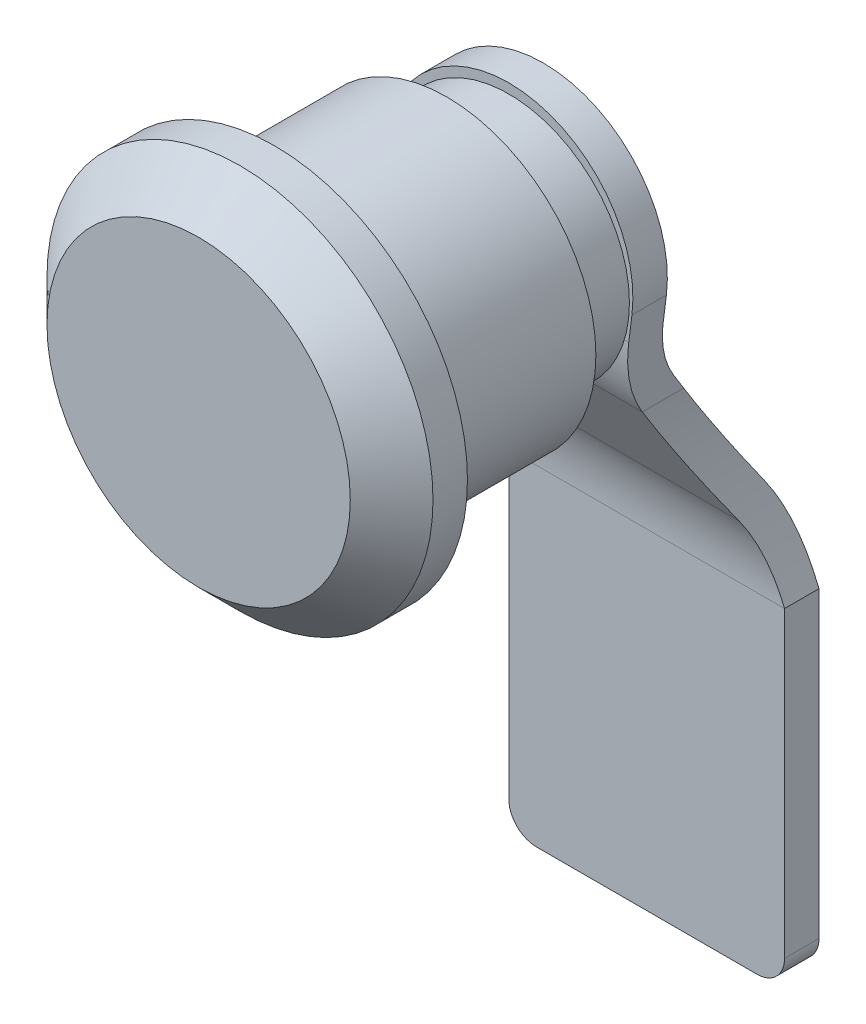
SolidWorks part; units mm, degrees
ref_plane "Front Plane" through (0, 0, 0) normal (1, 0, 0) x (0, 1, 0)
ref_plane "Top Plane" through (0, 0, 0) normal (0, 0, 1) x (0, 1, 0)
ref_plane "Right Plane" through (0, 0, 0) normal (0, 1, 0) x (-1, 0, 0)
sketch "Sketch1" plane through (0, 0, 0) normal (1, 0, 0) x (0, 1, 0)
  line L0 (0, 0) -> (23.9722, 0)
  line L1 (29.5192, 1.6795) -> (39.4808, 8.3205)
  line L2 (45.0278, 10) -> (57, 10)
  arc A0 (39.4808, 8.3205) -> (45.0278, 10) centre (45.0278, 0) cw
  arc A1 (23.9722, 0) -> (29.5192, 1.6795) centre (23.9722, 10) ccw
  point P3 (0, 0)
  point P8 (42, 10)
  point P12 (27, 0)
  point P14 (0, 0)
  dimension "D5" = 10
  dimension "D1" = 27
  dimension "D2" = 15
  dimension "D3" = 30
  dimension "D4" = 10
ref_plane "Plane1" through (0, 0, 0) normal (0, 1, 0) x (-1, 0, 0)
sketch "Sketch6" plane through (0, 0, 0) normal (0, 1, 0) x (-1, 0, 0)
  line L1 (-10, 0) -> (10, 0)
  line L2 (-10, 0) -> (-10, -2.5)
  line L3 (-10, -2.5) -> (10, -2.5)
  line L4 (10, 0) -> (10, -2.5)
  point P4 (0, 0)
  dimension "D1" = 2.5
  dimension "D2" = 20
sweep "Sweep1" add profiles "Sketch6" path "Sketch1"
sketch "Sketch18" plane through (0, 0, 10) normal (0, 0, 1) x (1, 0, 0)
  line L0 (0, 45.0278) -> (0, 57) construction
  line L1 (-10, 57) -> (10, 57) construction
  line L2 (-8.9297, 46.8776) -> (-8, 39.4808)
  line L3 (-10, 39.4808) -> (10, 39.4808) construction
  line L4 (8.9297, 46.8776) -> (8, 39.4808)
  line L5 (-10, 23.9722) -> (-10, 57)
  line L6 (-10, 57) -> (10, 57)
  line L7 (10, 57) -> (10, 23.9722)
  arc A0 (8.9297, 46.8776) -> (-8.9297, 46.8776) centre (0, 48) ccw
  arc A1 (-8, 39.4808) -> (-10, 23.9722) centre (-38.9564, 35.5897) cw
  arc A2 (8, 39.4808) -> (10, 23.9722) centre (38.9564, 35.5897) ccw
  point P1 (0, 0)
  point P6 (0, 0)
  line M4 (10, 57) -> (-10, 57)
  line M5 (-10, 57) -> (-10, 45.0278)
  line M6 (-10, 45.0278) -> (10, 45.0278)
  line M7 (10, 45.0278) -> (10, 57)
  dimension "D1" = 18
  dimension "D2" = 2
extrude "Cut-Extrude7" cut sketch "Sketch18" against normal through all contours A0 L4 M6 M7 M4 | L4 A2 L7 M6 | A0 L6 L2 M5 M6 | A1 L2 L5 M6
fillet "Fillet1" radius 2 2 edges at (10, 0, -1.25) (-10, 0, -1.25)
sketch "Sketch19" plane through (0, 0, 10) normal (0, 0, 1) x (1, 0, 0)
  line L0 (0, 45.0278) -> (0, 57) construction
  line L1 (-4.75, 52.3) -> (4.75, 52.3)
  line L2 (-4.75, 52.3) -> (-4.75, 42.8)
  line L3 (-4.75, 42.8) -> (4.75, 42.8)
  line L4 (4.75, 52.3) -> (4.75, 42.8)
  point P4 (0, 52.3)
  dimension "D1" = 9.5
  dimension "D2" = 4.7
extrude "Cut-Extrude8" cut sketch "Sketch19" against normal through all
sketch "Sketch20" plane through (0, 0, 10) normal (0, 0, 1) x (1, 0, 0)
  line L0 (0, 52.3) -> (0, 47.55) construction
  line L1 (4.75, 52.3) -> (-4.75, 52.3) construction
  line L2 (0, 45.0278) -> (0, 57) construction
  circle A0 centre (0, 47.55) radius 8.75
  dimension "D2" = 17.5
  dimension "D1" = 4.75
extrude "Boss-Extrude1" add sketch "Sketch20" along normal blind 4.5 separate body
sketch "Sketch21" plane through (0, 0, 14.5) normal (0, 0, 1) x (0, -1, 0)
  circle A0 centre (-47.55, 0) radius 10.815
  dimension "D1" = 21.63
extrude "Boss-Extrude2" add sketch "Sketch21" along normal blind 12.5
sketch "Sketch22" plane through (0, 0, 27) normal (0, 0, 1) x (1, 0, 0)
  circle A0 centre (0, 47.55) radius 14
  dimension "D1" = 28
extrude "Boss-Extrude3" add sketch "Sketch22" along normal blind 5.5
chamfer "Chamfer1" distance 3 angle 45 1 edges at (14, 47.55, 32.5)
